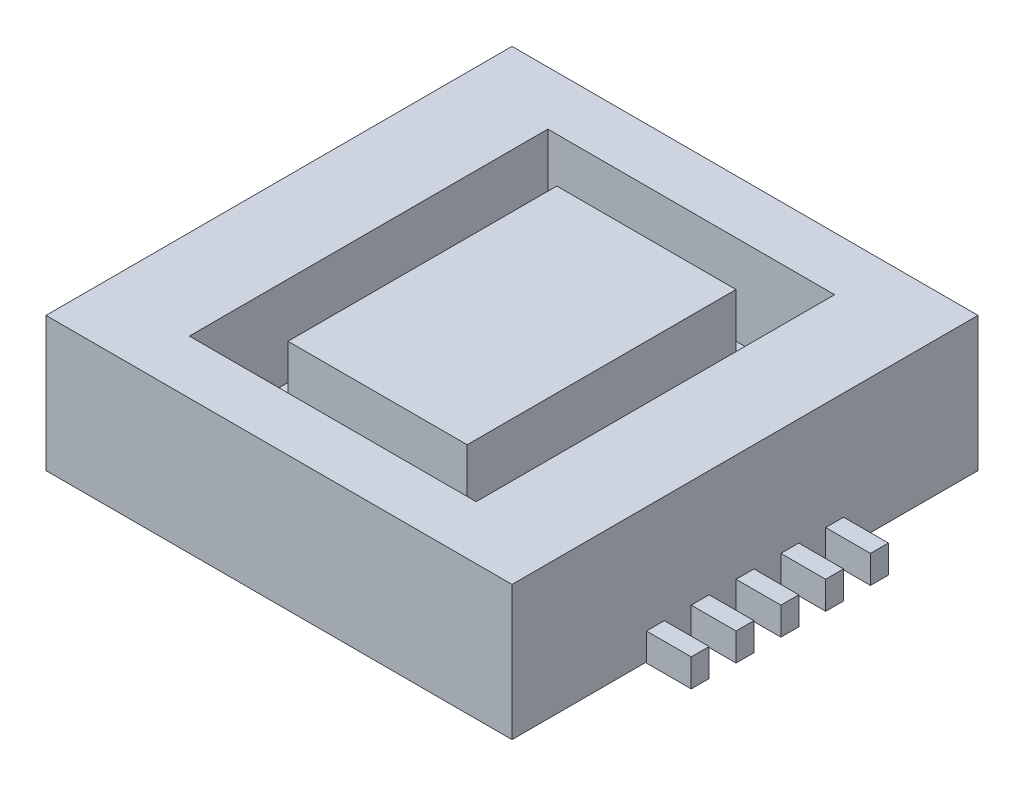
SolidWorks part; units mm, degrees
ref_plane "Спереди" through (0, 0, 0) normal (0, 0, 1) x (1, 0, 0)
ref_plane "Сверху" through (0, 0, 0) normal (0, 1, 0) x (1, 0, 0)
ref_plane "Справа" through (0, 0, 0) normal (1, 0, 0) x (0, 0, -1)
sketch "Эскиз1" plane through (0, 0, 0) normal (0, 1, 0) x (1, 0, 0)
  line L1 (-2.6, 2.6) -> (2.6, 2.6)
  line L2 (-2.6, 2.6) -> (-2.6, -2.6)
  line L3 (-2.6, -2.6) -> (2.6, -2.6)
  line L4 (2.6, 2.6) -> (2.6, -2.6)
  line L5 (-2.6, 2.6) -> (2.6, -2.6) construction
  line L6 (-2.6, -2.6) -> (2.6, 2.6) construction
  point P0 (0, 0)
  dimension "D1" = 5.2
extrude "Бобышка-Вытянуть1" add sketch "Эскиз1" along normal blind 1.5
sketch "Эскиз2" plane through (0, 1.5, 0) normal (0, 1, 0) x (1, 0, 0)
  line L1 (-1.6, 2) -> (1.6, 2)
  line L2 (-1.6, 2) -> (-1.6, -2)
  line L3 (-1.6, -2) -> (1.6, -2)
  line L4 (1.6, 2) -> (1.6, -2)
  line L5 (-1.6, 2) -> (1.6, -2) construction
  line L6 (-1.6, -2) -> (1.6, 2) construction
  line L7 (-1, 1.5) -> (1, 1.5)
  line L8 (-1, 1.5) -> (-1, -1.5)
  line L9 (-1, -1.5) -> (1, -1.5)
  line L10 (1, 1.5) -> (1, -1.5)
  line L11 (-1, 1.5) -> (1, -1.5) construction
  line L12 (-1, -1.5) -> (1, 1.5) construction
  point P0 (0, 0)
  point P5 (0, 0)
  dimension "D1" = 4
  dimension "D2" = 3.2
  dimension "D3" = 2
  dimension "D4" = 3
extrude "Вырез-Вытянуть1" cut sketch "Эскиз2" against normal blind 1
sketch "Эскиз3" plane through (0, 0, 0) normal (0, 1, 0) x (1, 0, 0)
  line L1 (-0.4, 0.1) -> (-3.1, 0.1)
  line L2 (-0.4, 0.1) -> (-0.4, -0.1)
  line L3 (-0.4, -0.1) -> (-3.1, -0.1)
  line L4 (-3.1, 0.1) -> (-3.1, -0.1)
  line L5 (-2.6, 2.6) -> (-2.6, -2.6) construction
  point P6 (-3.1, 0)
  dimension "D1" = 0.2
  dimension "D2" = 3.1
  dimension "D3" = 2.2
extrude "Бобышка-Вытянуть2" add sketch "Эскиз3" along normal blind 0.3 and the other way blind 0.01
pattern_linear "Линейный массив1" count 3 spacing 0.5 along (0, 0, -1) count 3 spacing 0.5 along (0, 0, 1) of "Бобышка-Вытянуть2"
mirror "Зеркальное отражение1" about plane through (0, 0, 0) normal (1, 0, 0) of "Линейный массив1", "Бобышка-Вытянуть2"
